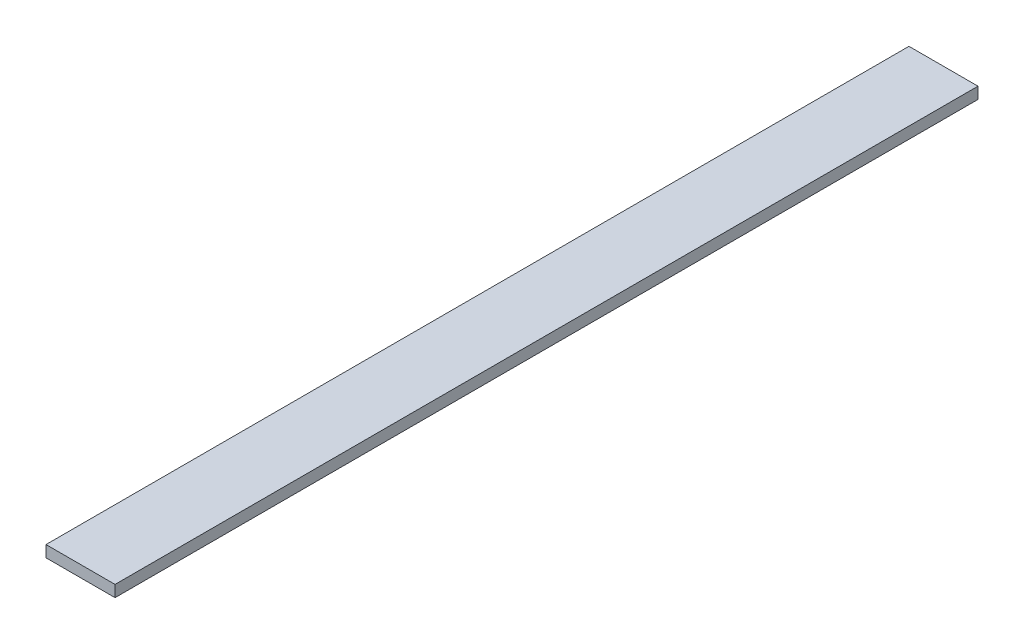
SolidWorks part; units mm, degrees
ref_plane "Front Plane" through (0, 0, 0) normal (0, 0, 1) x (1, 0, 0)
ref_plane "Top Plane" through (0, 0, 0) normal (0, 1, 0) x (1, 0, 0)
ref_plane "Right Plane" through (0, 0, 0) normal (1, 0, 0) x (0, 0, -1)
sketch "Sketch1" plane through (0, 0, 0) normal (0, 1, 0) x (1, 0, 0)
  line L1 (0, 0) -> (48, 0)
  line L2 (0, 0) -> (0, 600)
  line L3 (0, 600) -> (48, 600)
  line L4 (48, 0) -> (48, 600)
  dimension "D1" = 600
  dimension "D2" = 48
extrude "Boss-Extrude1" add sketch "Sketch1" along normal blind 8
